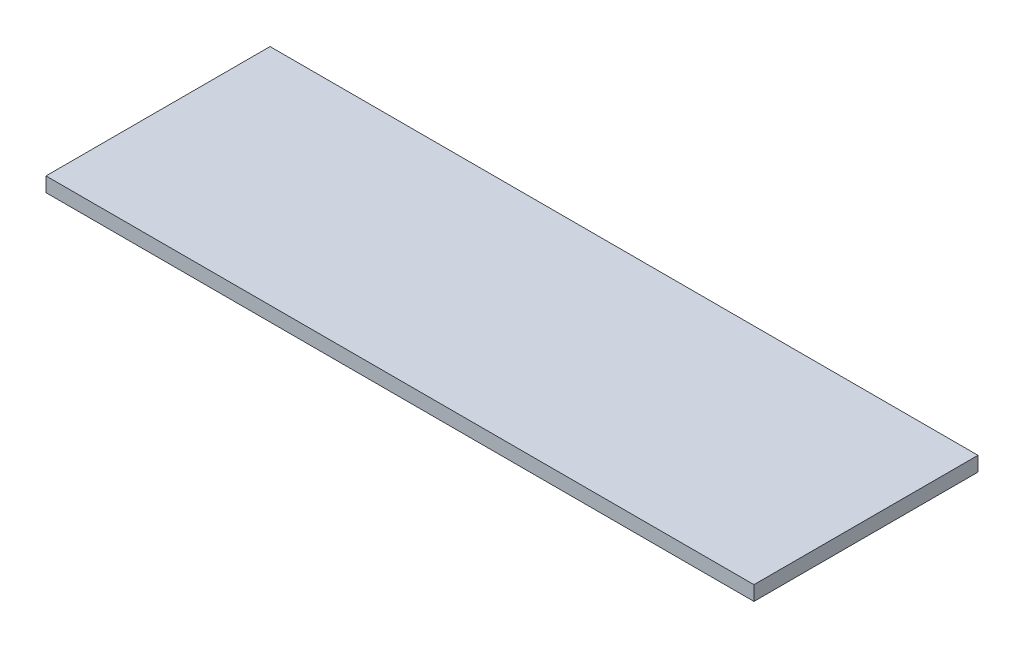
SolidWorks part; units mm, degrees
ref_plane "Front Plane" through (0, 0, 0) normal (0, 0, 1) x (1, 0, 0)
ref_plane "Top Plane" through (0, 0, 0) normal (0, 1, 0) x (1, 0, 0)
ref_plane "Right Plane" through (0, 0, 0) normal (1, 0, 0) x (0, 0, -1)
sketch "Sketch1" plane through (0, 0, 0) normal (0, 1, 0) x (1, 0, 0)
  line L1 (0, 0) -> (316, 0)
  line L2 (0, 0) -> (0, 100)
  line L3 (0, 100) -> (316, 100)
  line L4 (316, 0) -> (316, 100)
  dimension "D1" = 100
  dimension "D2" = 316
extrude "Boss-Extrude1" add sketch "Sketch1" along normal blind 6.5
